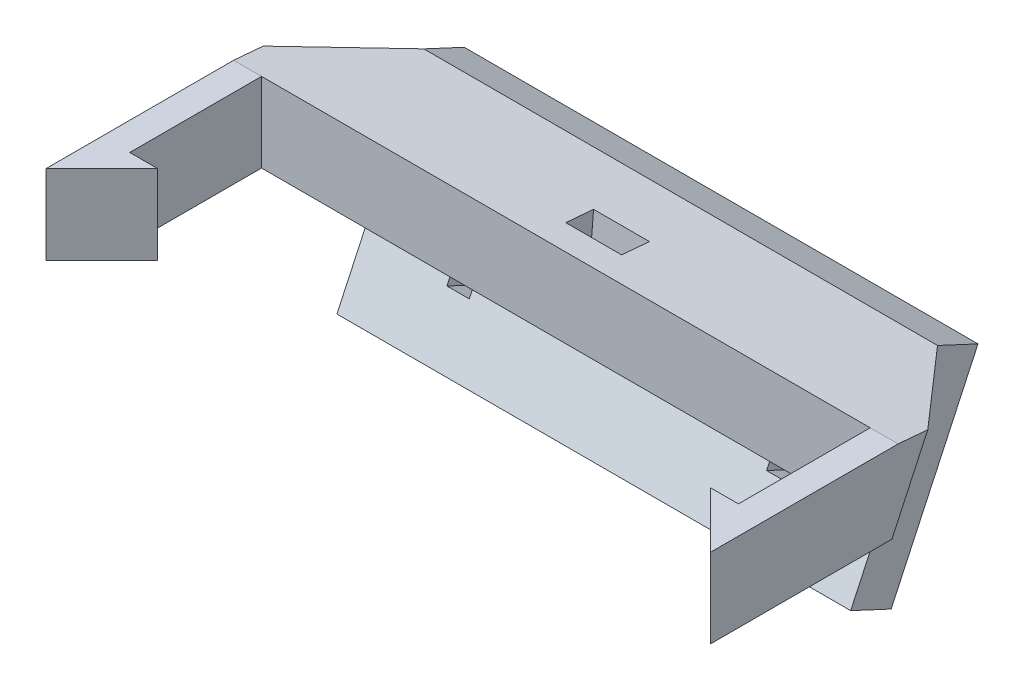
SolidWorks part; units mm, degrees
ref_plane "Front Plane" through (0, 0, 0) normal (0, 0, 1) x (1, 0, 0)
ref_plane "Top Plane" through (0, 0, 0) normal (0, 1, 0) x (1, 0, 0)
ref_plane "Right Plane" through (0, 0, 0) normal (1, 0, 0) x (0, 0, -1)
sketch "Sketch1" plane through (0, 0, 0) normal (0, 0, 1) x (1, 0, 0)
  line L1 (-37.7825, 17.78) -> (37.7825, 17.78)
  line L2 (-37.7825, 17.78) -> (-37.7825, -17.78)
  line L3 (-37.7825, -17.78) -> (37.7825, -17.78)
  line L4 (37.7825, 17.78) -> (37.7825, -17.78)
  point P4 (0, 17.78)
  point P6 (-37.7825, 0)
  dimension "D1" = 75.565
extrude "Boss-Extrude1" add sketch "Sketch1" against normal blind 3.175
sketch "Sketch6" plane through (0, 0, 0) normal (0, 0, 1) x (1, 0, 0)
  line L0 (-37.7825, 17.78) -> (-37.7825, -17.78) construction
  line L1 (-37.7825, 4.5142) -> (-34.6075, 4.5142)
  line L2 (-37.7825, 4.5142) -> (-37.7825, -4.5142)
  line L3 (-37.7825, -4.5142) -> (-34.6075, -4.5142)
  line L4 (-34.6075, 4.5142) -> (-34.6075, -4.5142)
  line L5 (37.7825, -17.78) -> (37.7825, 17.78) construction
  line L6 (37.7825, 4.5142) -> (34.6075, 4.5142)
  line L7 (37.7825, 4.5142) -> (37.7825, -4.5142)
  line L8 (37.7825, -4.5142) -> (34.6075, -4.5142)
  line L9 (34.6075, 4.5142) -> (34.6075, -4.5142)
  point P12 (37.7825, 0)
  point P14 (-37.7825, 0)
  dimension "D1" = 3.175
  dimension "D2" = 3.175
  dimension "D3" = 69.215
extrude "Boss-Extrude4" add sketch "Sketch6" along normal blind 14.986
sketch "Sketch8" plane through (0, -4.5142, 0) normal (0, -1, 0) x (1, 0, 0)
  line L0 (-37.7825, 14.986) -> (-31.4325, 14.986)
  line L1 (-31.4325, 14.986) -> (-37.7825, 21.336)
  line L2 (-37.7825, 21.336) -> (-37.7825, 14.986)
  line L3 (37.7825, 14.986) -> (31.4325, 14.986)
  line L4 (31.4325, 14.986) -> (37.7825, 21.336)
  line L5 (37.7825, 21.336) -> (37.7825, 14.986)
  dimension "D1" = 6.35
  dimension "D2" = 6.35
  dimension "D3" = 6.35
  dimension "D4" = 6.35
extrude "Boss-Extrude6" add sketch "Sketch8" against normal up to surface (9.0284 mm away) up to face at (-36.195, 4.5142, 7.493)
sketch "Sketch9" plane through (-37.7825, 0, 0) normal (-1, 0, 0) x (0, 0, 1)
  line L0 (-3.175, 17.78) -> (-16.7953, 11.4288)
  line L1 (-16.7953, 11.4288) -> (-3.175, -17.78)
  line L3 (-3.175, 17.78) -> (-3.175, -17.78) construction
  line L12 (0, 4.5142) -> (0, 17.78)
  line L13 (0, 17.78) -> (-3.175, 17.78)
  line L14 (-3.175, 17.78) -> (-3.175, -17.78)
  line L15 (-3.175, -17.78) -> (0, -17.78)
  line L16 (0, -17.78) -> (0, -4.5142)
  line L17 (0, -4.5142) -> (21.336, -4.5142)
  line L18 (21.336, -4.5142) -> (21.336, 4.5142)
  line L19 (21.336, 4.5142) -> (0, 4.5142)
  line L22 (-3.175, 17.78) -> (-3.175, -17.78)
  dimension "D1" = 90
  dimension "D2" = 25
  dimension "D3" = 0
extrude "Boss-Extrude7" add sketch "Sketch9" against normal up to surface (75.565 mm away) up to face at (37.7825, 0, 4.5403)
sketch "Sketch10" plane through (0, -4.3917, -9.4181) normal (0, -0.4226, -0.9063) x (-1, 0, 0)
  line L0 (37.7825, 17.456) -> (37.7825, -14.7723) construction
  line L1 (-37.7825, -14.7723) -> (37.7825, -14.7723)
  line L2 (-37.7825, -14.7723) -> (-37.7825, 8.5957)
  line L3 (-37.7825, 8.5957) -> (37.7825, 8.5957)
  line L4 (37.7825, -14.7723) -> (37.7825, 8.5957)
  dimension "D1" = 23.368
extrude "Boss-Extrude8" add sketch "Sketch10" along normal blind 5.08
sketch "Sketch11" plane through (-37.7825, 0, 0) normal (-1, 0, 0) x (0, 0, 1)
  line L0 (-13.0507, 3.3986) -> (0, 4.5142)
  line L1 (0, 4.5142) -> (36.8887, 18.2755)
  line L2 (36.8887, 18.2755) -> (5.2861, 25.1503)
  line L3 (5.2861, 25.1503) -> (-30.3838, 8.2332)
  line L4 (-30.3838, 8.2332) -> (-13.0507, 3.3986)
  line L5 (-3.175, -17.78) -> (-7.689, -8.0996)
  line L6 (-7.689, -8.0996) -> (0, -4.5142)
  line L7 (0, -4.5142) -> (40.1585, -20.4064)
  line L8 (40.1585, -20.4064) -> (15.5997, -25.3949)
  line L9 (15.5997, -25.3949) -> (-3.175, -17.78)
  line L10 (-7.779, -19.9269) -> (-17.6548, 1.2517) construction
  line L11 (-7.779, -19.9269) -> (-3.175, -17.78) construction
extrude "Cut-Extrude1" cut sketch "Sketch11" against normal through all
sketch "Sketch12" plane through (0, 4.4814, -0.3831) normal (0, 0.9964, -0.0852) x (1, 0, 0)
  line L0 (34.6075, -0.3845) -> (-34.6075, -0.3845) construction
  line L1 (-3.175, 5.9655) -> (3.175, 5.9655)
  line L2 (-3.175, 5.9655) -> (-3.175, 2.7905)
  line L3 (-3.175, 2.7905) -> (3.175, 2.7905)
  line L4 (3.175, 5.9655) -> (3.175, 2.7905)
  point P6 (0, 2.7905)
  point P7 (0, -0.3845)
  dimension "D1" = 3.175
  dimension "D2" = 6.35
  dimension "D3" = 3.175
extrude "Cut-Extrude2" cut sketch "Sketch12" against normal up to next and the other way through all
sketch "Sketch13" plane through (0, 7.7903, -3.6327) normal (0, 0.9063, -0.4226) x (1, 0, 0)
  line L0 (0, 10.3917) -> (0, 15.4717) construction
  line L1 (-37.7825, 10.3917) -> (37.7825, 10.3917) construction
  line L2 (-37.7825, 15.4717) -> (37.7825, 15.4717) construction
  line L3 (-29.21, 10.3917) -> (-37.7825, 1.2672)
  line L4 (-37.7825, 15.4717) -> (-29.21, 15.4717)
  line L5 (-37.7825, 15.4717) -> (-37.7825, 11.6396)
  line L6 (37.7825, 1.2672) -> (37.7825, 11.6396)
  line L7 (-29.21, 15.4717) -> (-29.21, 10.3917)
  line L8 (-37.7825, 1.2672) -> (-37.7825, 11.6396)
  line L9 (37.7825, 15.4717) -> (37.7825, 11.6396)
  line L10 (37.7825, 15.4717) -> (29.21, 15.4717)
  line L11 (29.21, 10.3917) -> (37.7825, 1.2672)
  line L12 (29.21, 15.4717) -> (29.21, 10.3917)
  line L13 (-37.7825, 10.3917) -> (-37.7825, -1.9078) construction
  dimension "D1" = 29.21
  dimension "D2" = 3.175
extrude "Cut-Extrude3" cut sketch "Sketch13" against normal through all
sketch "Sketch14" plane through (0, -6.5386, -14.0221) normal (0, -0.4226, -0.9063) x (-1, 0, 0)
  line L0 (-29.21, -4.1779) -> (29.4553, -4.1779) construction
  line L1 (-29.21, -14.7723) -> (-29.21, 8.5957) construction
  line L2 (0.1227, -4.1779) -> (0.1227, -14.7723) construction
  line L3 (-19.3205, -4.1779) -> (-16.7805, -4.1779)
  line L4 (-19.3205, -4.1779) -> (-19.3205, -7.9879)
  line L5 (-19.3205, -7.9879) -> (-16.7805, -7.9879)
  line L6 (-16.7805, -4.1779) -> (-16.7805, -7.9879)
  line L7 (-29.21, -14.7723) -> (29.21, -14.7723) construction
  line L8 (19.5659, -4.1779) -> (17.0259, -4.1779)
  line L9 (17.0259, -4.1779) -> (17.0259, -7.9879)
  line L10 (19.5659, -7.9879) -> (17.0259, -7.9879)
  line L11 (19.5659, -4.1779) -> (19.5659, -7.9879)
  dimension "D1" = 2.54
  dimension "D2" = 3.81
extrude "Cut-Extrude4" cut sketch "Sketch14" against normal up to next
